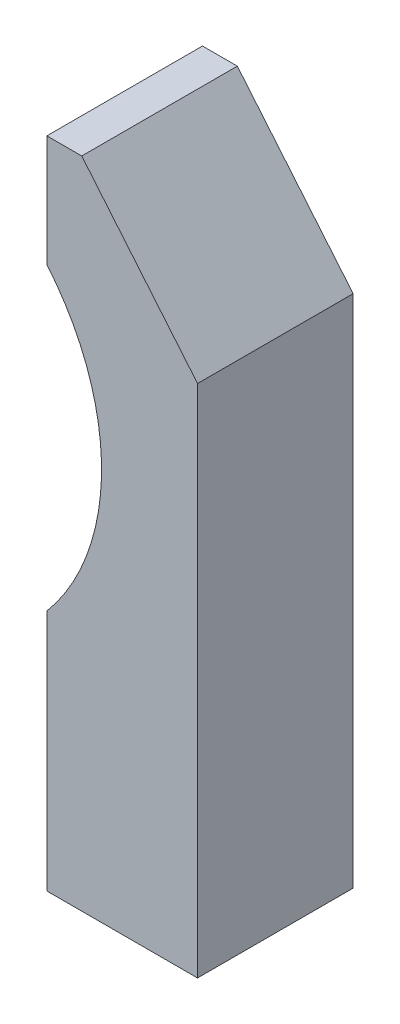
SolidWorks part; units mm, degrees
material "6061-T6 (SS)"
ref_plane "Front Plane" through (0, 0, 0) normal (0, 0, 1) x (1, 0, 0)
ref_plane "Top Plane" through (0, 0, 0) normal (0, 1, 0) x (1, 0, 0)
ref_plane "Right Plane" through (0, 0, 0) normal (1, 0, 0) x (0, 0, -1)
sketch "Sketch1" plane through (0, 0, 0) normal (0, 0, 1) x (1, 0, 0)
  line L0 (0, 0) -> (31.9685, 0)
  line L1 (31.9685, 0) -> (31.9685, 109.243)
  line L2 (0, 0) -> (0, 51.4592)
  line L3 (0, 138.7712) -> (7.3993, 138.7712)
  line L4 (7.3993, 138.7712) -> (31.9685, 109.243)
  line L5 (0, 115.1068) -> (0, 138.7712)
  arc A0 (0, 51.4592) -> (0, 115.1068) centre (-37.8268, 83.283) ccw
extrude "Boss-Extrude1" add sketch "Sketch1" along normal blind 33.02
